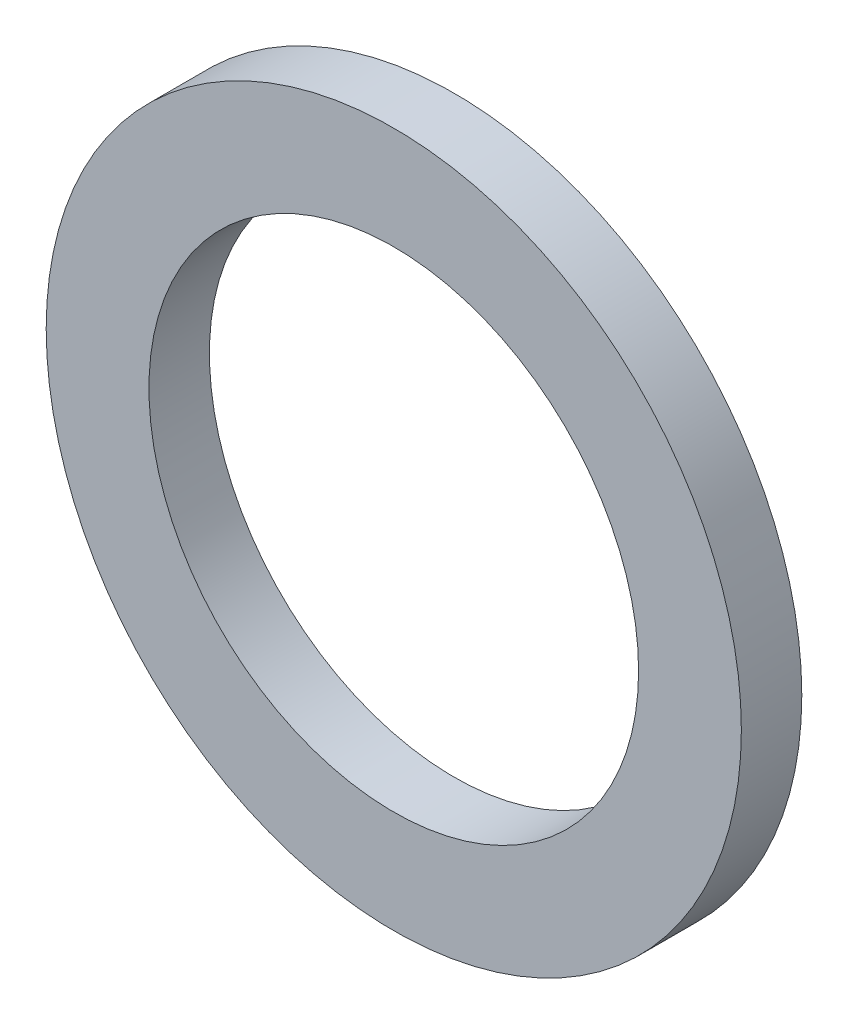
SolidWorks part; units mm, degrees
ref_plane "Front Plane" through (0, 0, 0) normal (0, 0, 1) x (1, 0, 0)
ref_plane "Top Plane" through (0, 0, 0) normal (0, 1, 0) x (1, 0, 0)
ref_plane "Right Plane" through (0, 0, 0) normal (1, 0, 0) x (0, 0, -1)
sketch "Sketch1" plane through (0, 0, 0) normal (0, 0, 1) x (1, 0, 0)
  circle A0 centre (0, 0) radius 5.75
  circle A1 centre (0, 0) radius 4.05
  dimension "D1" = 11.5
  dimension "D2" = 8.1
extrude "Boss-Extrude1" add sketch "Sketch1" along normal blind 1
